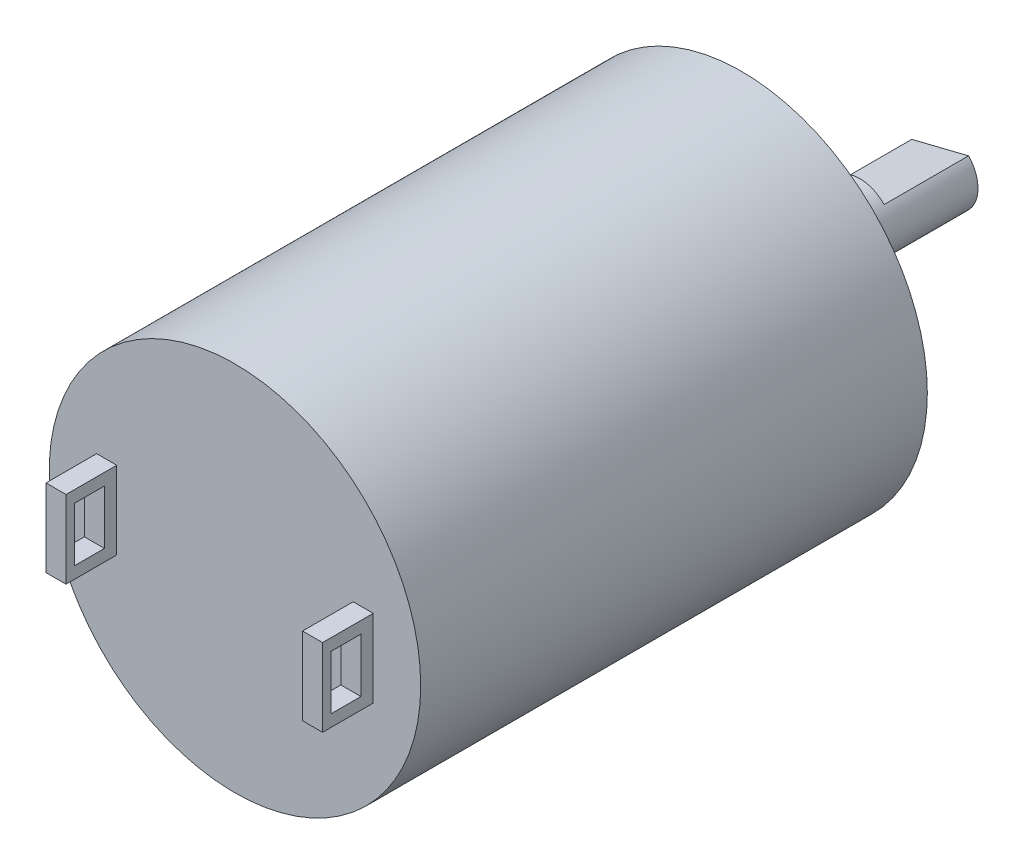
SolidWorks part; units mm, degrees
ref_plane "Front Plane" through (0, 0, 0) normal (0, 0, 1) x (1, 0, 0)
ref_plane "Top Plane" through (0, 0, 0) normal (0, 1, 0) x (1, 0, 0)
ref_plane "Right Plane" through (0, 0, 0) normal (1, 0, 0) x (0, 0, -1)
sketch "Sketch1" plane through (0, 0, 0) normal (0, 0, 1) x (1, 0, 0)
  circle A0 centre (0, 0) radius 11
extrude "Boss-Extrude1" add sketch "Sketch1" along normal blind 30
sketch "Sketch2" plane through (0, 0, 0) normal (0, 0, -1) x (-1, 0, 0)
  circle A0 centre (0, 0) radius 3
extrude "Boss-Extrude2" add sketch "Sketch2" along normal blind 2
sketch "Sketch3" plane through (0, 0, -2) normal (0, 0, -1) x (-1, 0, 0)
  circle A0 centre (0, 0) radius 2
  dimension "D1" = 4
extrude "Boss-Extrude3" add sketch "Sketch3" along normal blind 10
sketch "Sketch4" plane through (0, 0, 30) normal (0, 0, 1) x (1, 0, 0)
  line L0 (0, 0) -> (0, 7.4287) construction
  line L1 (-8.1883, -2.3009) -> (-7.001, -2.3009)
  line L2 (-8.1883, -2.3009) -> (-8.1883, 2.3009)
  line L3 (-8.1883, 2.3009) -> (-7.001, 2.3009)
  line L4 (-7.001, -2.3009) -> (-7.001, 2.3009)
  line L5 (-8.1883, -2.3009) -> (-7.001, 2.3009) construction
  line L6 (-8.1883, 2.3009) -> (-7.001, -2.3009) construction
  line L7 (8.1883, 2.3009) -> (7.001, -2.3009) construction
  line L8 (8.1883, -2.3009) -> (8.1883, 2.3009)
  line L9 (8.1883, 2.3009) -> (7.001, 2.3009)
  line L10 (8.1883, -2.3009) -> (7.001, 2.3009) construction
  line L11 (7.001, -2.3009) -> (7.001, 2.3009)
  line L12 (8.1883, -2.3009) -> (7.001, -2.3009)
  point P0 (-7.5947, 0)
extrude "Boss-Extrude4" add sketch "Sketch4" along normal blind 3
sketch "Sketch5" plane through (-8.1883, 0, 0) normal (-1, 0, 0) x (0, 0, 1)
  line L0 (33, 2.3009) -> (30, 2.3009) construction
  line L1 (30.7287, 1.6009) -> (32.5, 1.6009)
  line L2 (30.7287, 1.6009) -> (30.7287, -1.6009)
  line L3 (30.7287, -1.6009) -> (32.5, -1.6009)
  line L4 (32.5, 1.6009) -> (32.5, -1.6009)
  line L5 (30.7287, 1.6009) -> (32.5, -1.6009) construction
  line L6 (30.7287, -1.6009) -> (32.5, 1.6009) construction
  line L7 (33, -2.3009) -> (30, -2.3009) construction
  line L8 (33, 2.3009) -> (33, -2.3009) construction
  point P0 (31.6143, 0)
  dimension "D1" = 0.7
  dimension "D2" = 0.7
  dimension "D3" = 0.5
extrude "Cut-Extrude1" cut sketch "Sketch5" against normal through all
sketch "Sketch6" plane through (0, 0, -12) normal (0, 0, -1) x (-1, 0, 0)
  line L0 (-1.4399, 1.3881) -> (1.9221, 0.5529)
  circle A0 centre (0, 0) radius 2 construction
  circle A1 centre (0, 0) radius 2
  circle M2 centre (0, 0) radius 2
  dimension "D1" = 1
extrude "Cut-Extrude2" cut sketch "Sketch6" against normal blind 5 contours L0 M2
